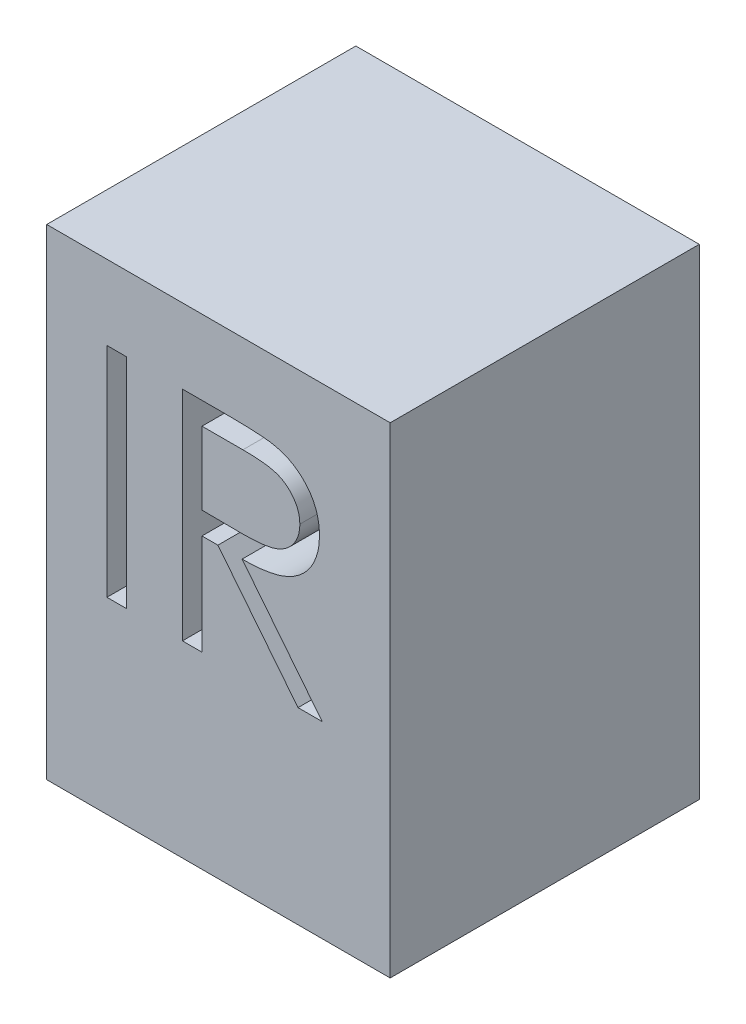
SolidWorks part; units mm, degrees
ref_plane "Front Plane" through (0, 0, 0) normal (0, 0, 1) x (1, 0, 0)
ref_plane "Top Plane" through (0, 0, 0) normal (0, 1, 0) x (1, 0, 0)
ref_plane "Right Plane" through (0, 0, 0) normal (1, 0, 0) x (0, 0, -1)
sketch "Sketch1" plane through (0, 0, 0) normal (0, 0, 1) x (1, 0, 0)
  line L1 (0, 0) -> (5, 0)
  line L2 (0, 0) -> (0, 7)
  line L3 (0, 7) -> (5, 7)
  line L4 (5, 0) -> (5, 7)
  dimension "D1" = 7
  dimension "D2" = 5
extrude "Boss-Extrude1" add sketch "Sketch1" along normal blind 4.5
sketch "Sketch2" plane through (0, 0, 4.5) normal (0, 0, 1) x (1, 0, 0)
  text T0 "IR"
extrude "Cut-Extrude1" cut sketch "Sketch2" against normal blind 1.27
